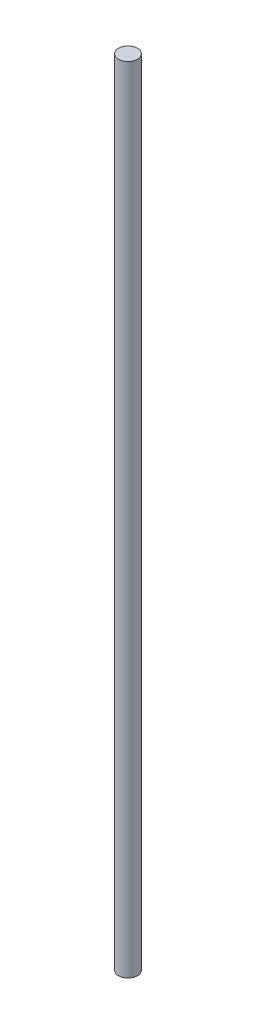
SolidWorks part; units mm, degrees
ref_plane "Front Plane" through (0, 0, 0) normal (0, 0, 1) x (1, 0, 0)
ref_plane "Top Plane" through (0, 0, 0) normal (0, 1, 0) x (1, 0, 0)
ref_plane "Right Plane" through (0, 0, 0) normal (1, 0, 0) x (0, 0, -1)
sketch "Sketch2" plane through (0, 0, 0) normal (0, 1, 0) x (1, 0, 0)
  circle A0 centre (0, 0) radius 1.5
  dimension "D1" = 3
extrude "Boss-Extrude1" add sketch "Sketch2" along normal blind 125
